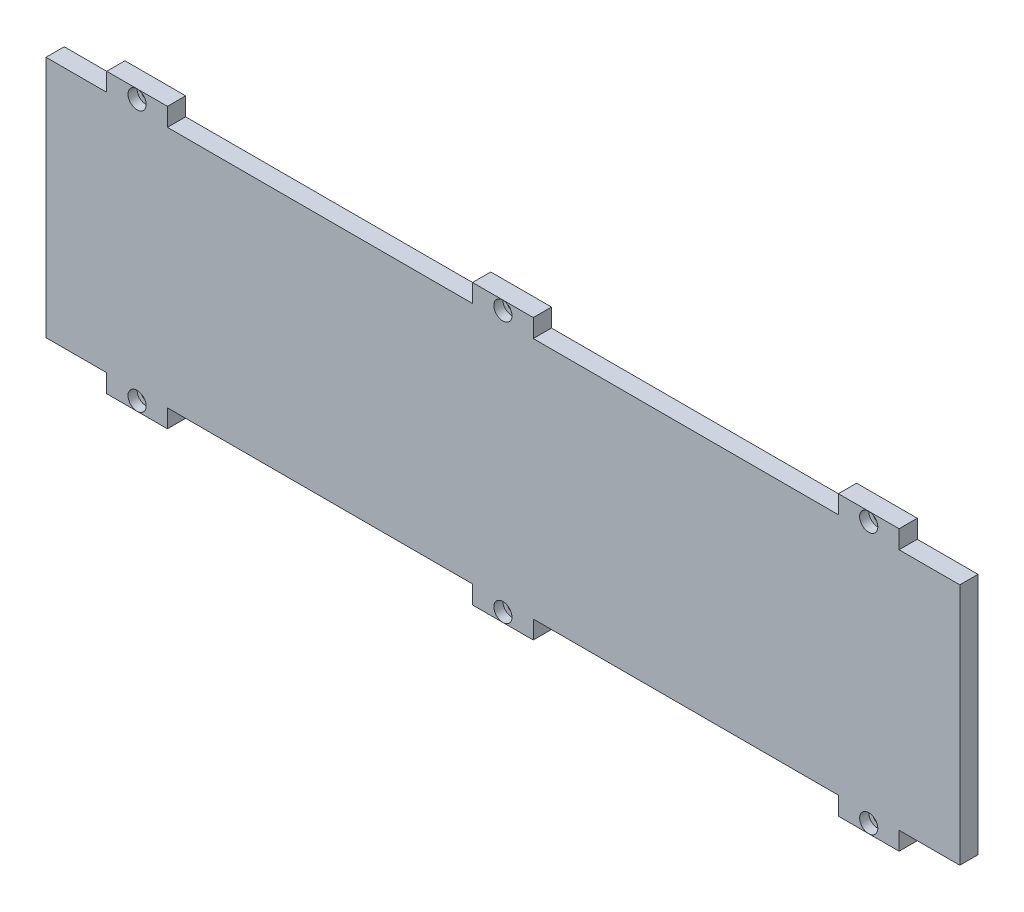
SolidWorks part; units mm, degrees
ref_plane "Plan de face" through (0, 0, 0) normal (0, 0, 1) x (1, 0, 0)
ref_plane "Plan de dessus" through (0, 0, 0) normal (0, 1, 0) x (1, 0, 0)
ref_plane "Plan de droite" through (0, 0, 0) normal (1, 0, 0) x (0, 0, -1)
sketch "Esquisse1" plane through (0, 0, 0) normal (0, 0, 1) x (1, 0, 0)
  line L0 (-301, 40) -> (0, 40) construction
  line L1 (-40, 80) -> (-140.5, 80)
  line L2 (0, 0) -> (0, 80)
  line L3 (0, 80) -> (-20, 80)
  line L4 (-301, 0) -> (-301, 80)
  line L5 (-301, 86) -> (0, 86) construction
  line L6 (-281, 80) -> (-301, 80)
  line L7 (-160.5, 80) -> (-261, 80)
  line L8 (-281, 80) -> (-281, 86)
  line L9 (-281, 86) -> (-261, 86)
  line L10 (-261, 80) -> (-261, 86)
  line L11 (-261, 0) -> (-261, -6)
  line L12 (-160.5, 80) -> (-160.5, 86)
  line L13 (-160.5, 86) -> (-140.5, 86)
  line L14 (-140.5, 80) -> (-140.5, 86)
  line L15 (-281, -6) -> (-261, -6)
  line L16 (-40, 80) -> (-40, 86)
  line L17 (-40, 86) -> (-20, 86)
  line L18 (-20, 80) -> (-20, 86)
  line L19 (-281, 0) -> (-281, -6)
  line L20 (-281, 0) -> (-301, 0)
  line L21 (-160.5, 0) -> (-261, 0)
  line L22 (-160.5, 0) -> (-160.5, -6)
  line L23 (-160.5, -6) -> (-140.5, -6)
  line L24 (-140.5, 0) -> (-140.5, -6)
  line L25 (-40, 0) -> (-140.5, 0)
  line L26 (0, 0) -> (-20, 0)
  line L27 (-20, 0) -> (-20, -6)
  line L28 (-40, -6) -> (-20, -6)
  line L29 (-40, 0) -> (-40, -6)
  dimension "D1" = 80
  dimension "D2" = 301
  dimension "D3" = 6
  dimension "D4" = 20
  dimension "D5" = 20
  dimension "D6" = 20
  dimension "D7" = 20
  dimension "D8" = 20
  dimension "D9" = 100.5
extrude "Boss.-Extru.1" add sketch "Esquisse1" along normal blind 6
sketch "Esquisse2" plane through (0, 0, 6) normal (0, 0, 1) x (1, 0, 0)
  line L0 (-301, 40) -> (0, 40) construction
  line L1 (-301, 80) -> (-301, 0) construction
  line L2 (0, 0) -> (0, 80) construction
  line L3 (-140.5, 80) -> (-140.5, 86) construction
  line L4 (-40, 86) -> (-40, 80) construction
  line L5 (-261, 80) -> (-261, 86) construction
  line L6 (-261, 86) -> (-281, 86) construction
  line L7 (-140.5, 86) -> (-160.5, 86) construction
  line L8 (-20, 86) -> (-40, 86) construction
  circle A0 centre (-271, 83) radius 1.5
  circle A1 centre (-150.5, 83) radius 1.5
  circle A2 centre (-30, 83) radius 1.5
  circle A3 centre (-271, -3) radius 1.5
  circle A4 centre (-150.5, -3) radius 1.5
  circle A5 centre (-30, -3) radius 1.5
  point P12 (-140.5, 83)
  point P15 (-40, 83)
  point P18 (-261, 83)
  dimension "D1" = 3
  dimension "D2" = 3
  dimension "D5" = 3
  dimension "D3" = 10
  dimension "D4" = 10
  dimension "D6" = 10
  dimension "D7" = 3
  dimension "D8" = 3
  dimension "D9" = 3
extrude "Enlèv. mat.-Extru.1" cut sketch "Esquisse2" against normal through all
sketch "Esquisse3" plane through (0, 0, 6) normal (0, 0, 1) x (1, 0, 0)
  line L0 (0, 40) -> (-301, 40) construction
  line L1 (0, 0) -> (0, 80) construction
  line L2 (-301, 80) -> (-301, 0) construction
  circle A0 centre (-271, 83) radius 2.995
  circle A1 centre (-150.5, 83) radius 2.995
  circle A2 centre (-30, 83) radius 2.995
  circle A3 centre (-30, -3) radius 2.995
  circle A4 centre (-150.5, -3) radius 2.995
  circle A5 centre (-271, -3) radius 2.995
  dimension "D1" = 5.99
  dimension "D2" = 5.99
  dimension "D3" = 5.99
extrude "Enlèv. mat.-Extru.2" cut sketch "Esquisse3" against normal blind 3
